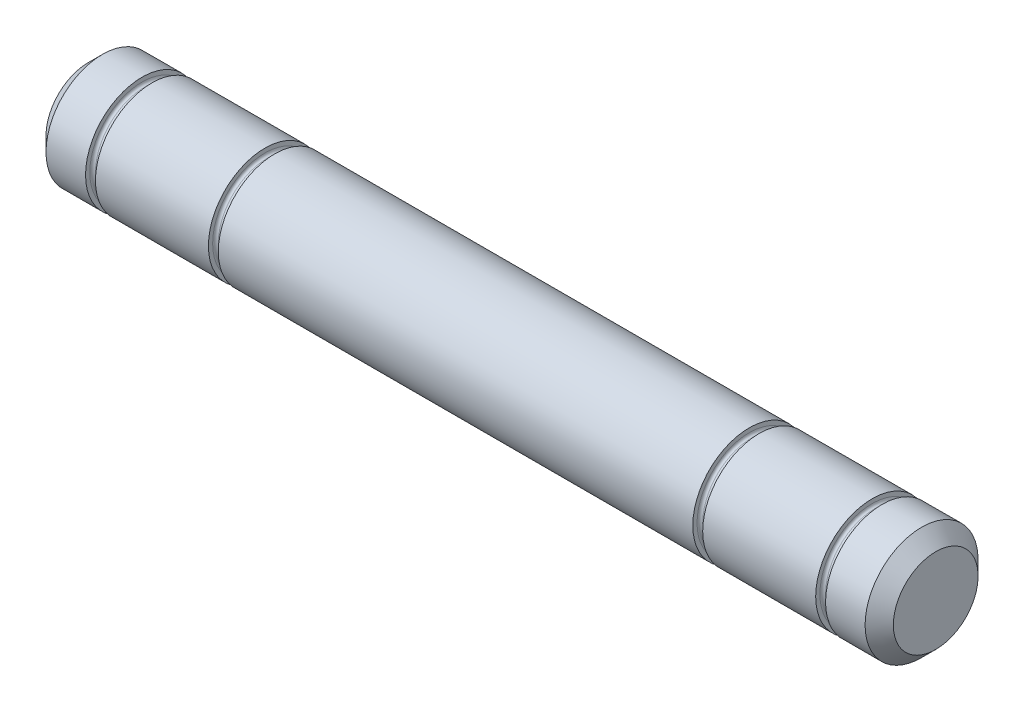
SolidWorks part; units mm, degrees
ref_plane "Front Plane" through (0, 0, 0) normal (0, 0, 1) x (1, 0, 0)
ref_plane "Top Plane" through (0, 0, 0) normal (0, 1, 0) x (1, 0, 0)
ref_plane "Right Plane" through (0, 0, 0) normal (1, 0, 0) x (0, 0, -1)
sketch "Sketch1" plane through (0, 0, 0) normal (0, 0, 1) x (1, 0, 0)
  line L1 (-30, 4) -> (30, 4)
  line L2 (-30, 4) -> (-30, 0)
  line L3 (-30, 0) -> (30, 0)
  line L4 (30, 4) -> (30, 0)
  dimension "D1" = 60
  dimension "D2" = 4
revolve "Revolve1" add sketch "Sketch1" angle 360 about L3
chamfer "Chamfer1" distance 1 angle 45 2 edges at (30, 0, 4) (-30, 0, 4)
sketch "Sketch2" plane through (0, 0, 0) normal (0, 1, 0) x (1, 0, 0)
  line L10 (0, 0) -> (36.1737, 0) construction
  line L11 (25.7, -3.5) -> (26, -3.5)
  line L12 (25.5, -3.7) -> (25.5, -4.8)
  line L13 (25.5, -4.8) -> (26.2, -4.8)
  line L14 (26.2, -3.7) -> (26.2, -4.8)
  line L15 (17, -3.5) -> (17.3, -3.5)
  line L16 (16.8, -3.7) -> (16.8, -4.8)
  line L17 (16.8, -4.8) -> (17.5, -4.8)
  line L18 (17.5, -3.7) -> (17.5, -4.8)
  arc A0 (25.7, -3.5) -> (25.5, -3.7) centre (25.7, -3.7) ccw
  arc A1 (26, -3.5) -> (26.2, -3.7) centre (26, -3.7) cw
  arc A2 (17, -3.5) -> (16.8, -3.7) centre (17, -3.7) ccw
  arc A3 (17.3, -3.5) -> (17.5, -3.7) centre (17.3, -3.7) cw
  point P17 (17.5, -3.5)
  dimension "D6" = 0.2
  dimension "D1" = 0.7
  dimension "D2" = 1.3
  dimension "D3" = 8
  dimension "D4" = 25.5
  dimension "D5" = 3.5
revolve "Cut-Revolve1" cut sketch "Sketch2" angle 360 about L10
mirror "Mirror1" about plane through (0, 0, 0) normal (1, 0, 0) of "Cut-Revolve1"
